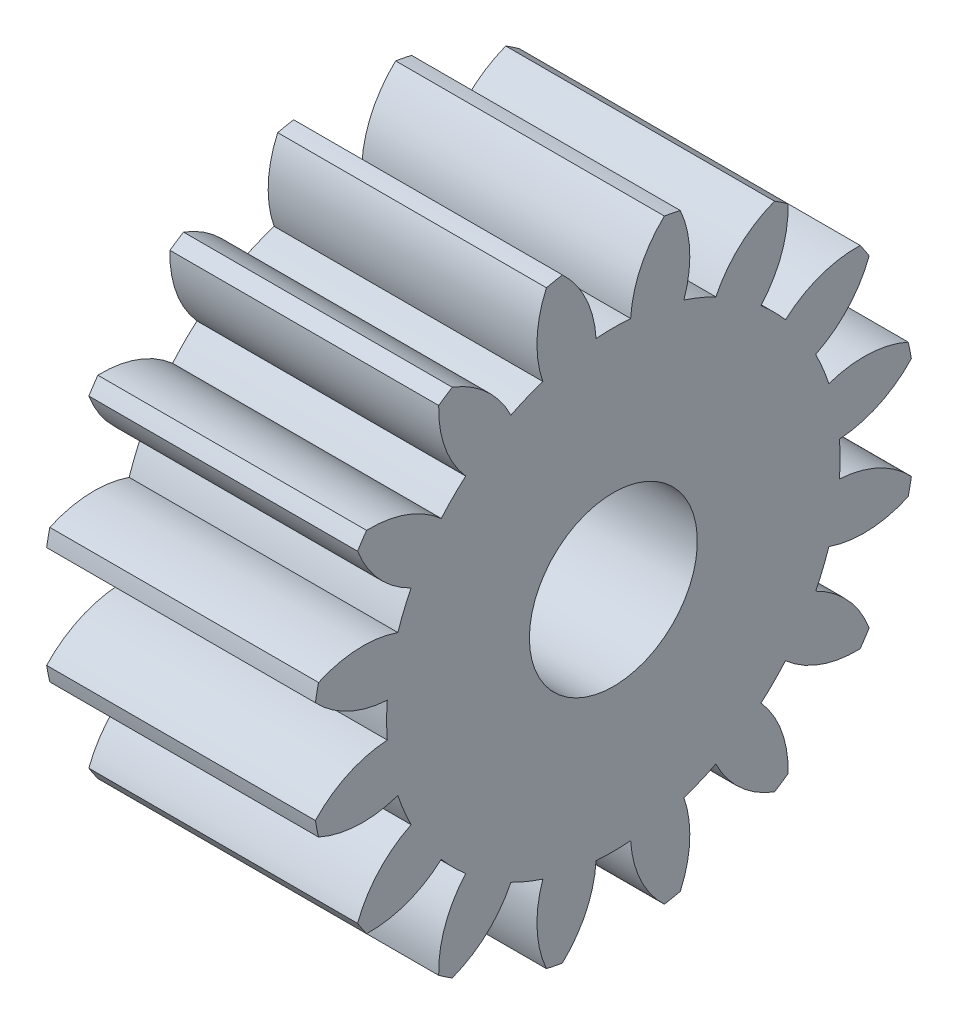
SolidWorks part; units mm, degrees
ref_plane "Plane1" through (0, 0, 0) normal (0, 0, 1) x (1, 0, 0)
ref_plane "Plane2" through (0, 0, 0) normal (0, 1, 0) x (1, 0, 0)
ref_plane "Plane3" through (0, 0, 0) normal (1, 0, 0) x (0, 0, -1)
sketch "HoldingSke" plane through (0, 0, 0) normal (0, 1, 0) x (1, 0, 0)
  line L0 (0, 0) -> (0.2403, -0.0689)
  line L1 (-15, 0) -> (100, 0) construction
  line L2 (0, 0) -> (-2.1039, 2.3779)
  line L3 (0, 0) -> (-11.863, 4.5341)
  line L4 (0, 0) -> (8.3015, 2.3804)
  line L5 (0, 0) -> (-46.8476, -17.4728)
  line L6 (0, 0) -> (-20.7241, -13.9826)
  line L7 (-2.1039, 2.3779) -> (8.6586, 51.2059)
  line L8 (-76.2, 54.61) -> (-73.4, 54.61)
  line L9 (-71.009, 38.7566) -> (-53.1078, 45.2721)
  line L10 (-76.2, 71.12) -> (104.1128, 71.12)
  line L11 (0, 0) -> (-25, 0)
  line L12 (-76.2, 101.6) -> (-76.073, 101.6)
  line L13 (24.9733, 27.94) -> (52.9518, 28.4284)
  line L14 (24.9733, 27.94) -> (24.9743, 27.94)
  line L15 (24.9733, 27.94) -> (100.4006, 29.5858)
  line L16 (-63.627, -4) -> (-12.827, -4)
  circle A0 centre (0, 0) radius 10
  circle A1 centre (0, 0) radius 26.999
  circle A2 centre (0, 0) radius 37.5
  circle A3 centre (0, 0) radius 10
  dimension "MHD" = 53.998
  dimension "Hub_dia" = 75
  dimension "Bore" = 20
  dimension "MBD" = 20
  dimension "Num_teeth" = 16
  dimension "Pitch" = 0.25
  dimension "Overall_len" = 50
  dimension "Show_teeth" = 16
  dimension "Thickness" = 25
  dimension "OAL" = 50.0001
  dimension "T_dim" = 2.8
  dimension "Ap" = 20
  dimension "H" = 19.05
  dimension "Pitch_radius" = 180.3128
  dimension "Width" = 25
  dimension "Backlash" = 0.127
  dimension "Addendum_fac" = 1
  dimension "Dedendum_fac" = 1.25
  dimension "Clearance_fac" = 0.25
  dimension "Dedendum_add" = 0.001
  dimension "Module" = 4
sketch "BasProSke" plane through (0, 0, 0) normal (0, 1, 0) x (1, 0, 0)
  line L0 (-10, 0) -> (60, 0) construction
  line L1 (0, 0) -> (0, 36)
  line L2 (0, 0) -> (32, 0)
  line L3 (32, 0) -> (32, 36)
  line L4 (32, 36) -> (0, 36)
  dimension "Thickness" = 32
  dimension "Diameter" = 72
revolve "Base-Revolve" add sketch "BasProSke" angle 360 about L0
sketch "TooCutSke" plane through (0, 0, 0) normal (1, 0, 0) x (0, 0, -1)
  line L1 (0, 0) -> (0, 107) construction
  line L2 (0, 0) -> (-3.3586, 31.8233) construction
  line L3 (0, 0) -> (-12.4339, 62.5094) construction
  line L4 (-3.3586, 31.8233) -> (-6.2169, 31.2547) construction
  arc A0 (2.0584, 26.9204) -> (-2.0584, 26.9204) centre (0, 0) ccw
  arc A1 (6.0943, 35.5062) -> (-6.0943, 35.5062) centre (0, 0) ccw
  circle A2 centre (0, 0) radius 32 construction
  circle A3 centre (0, 0) radius 30.0702 construction
  arc A4 (-2.0584, 26.9204) -> (-6.0943, 35.5062) centre (-14.8355, 26.1557) ccw
  arc A5 (6.0943, 35.5062) -> (2.0584, 26.9204) centre (14.8355, 26.1557) ccw
  dimension "Root_dia" = 53.998
  dimension "Overcut_dia" = 72.0508
  dimension "Pitch_dia" = 64
  dimension "Base_dia" = 60.1403
  dimension "Flank_rad" = 12.8
  dimension "Half_ang" = 11.25
  dimension "Half_CT" = 2.9143
extrude "ToothCut" cut sketch "TooCutSke" along normal through all
fillet "Breaks" [suppressed] radius 0.08
fillet "RootFillets" [suppressed] radius 1.001
pattern_circular "TeethCuts" count 16 every 22.5 about axis through (-10, 0, 0) along (1, 0, 0) of "ToothCut", "RootFillets", "Breaks"
sketch "HubNeaOneSke" plane through (0, 0, 0) normal (-1, 0, 0) x (0, 0, 1)
  circle A0 centre (0, 0) radius 26.999
  dimension "Diameter" = 53.998
extrude "HubNearOne" [suppressed] add sketch "HubNeaOneSke" along normal blind 18.0001
sketch "HubNeaBotSke" plane through (0, 0, 0) normal (-1, 0, 0) x (0, 0, 1)
  circle A0 centre (0, 0) radius 26.999
  dimension "Diameter" = 53.998
extrude "HubNearBoth" [suppressed] add sketch "HubNeaBotSke" along normal blind 9
ref_plane "FarPln" through (32, 0, 0) normal (1, 0, 0) x (0, 0, -1)
sketch "HubFarSke" plane through (32, 0, 0) normal (1, 0, 0) x (0, 0, -1)
  circle A0 centre (0, 0) radius 26.999
  dimension "Diameter" = 53.998
extrude "HubFar" [suppressed] add sketch "HubFarSke" along normal blind 9
sketch "BorSke" plane through (0, 0, 0) normal (1, 0, 0) x (0, 0, -1)
  circle A0 centre (0, 0) radius 10
  dimension "Diameter" = 20
extrude "Bore" cut sketch "BorSke" along normal mid plane 100.0001
sketch "KeySke" plane through (0, 0, 0) normal (1, 0, 0) x (0, 0, -1)
  line L0 (-3, 0) -> (-3, 12.8)
  line L1 (-3, 12.8) -> (3, 12.8)
  line L2 (3, 12.8) -> (3, 0)
  line L3 (0, 0) -> (0, 34) construction
  line L4 (-3, 0) -> (3, 0)
  dimension "Offset" = 12.8
  dimension "Width" = 6
extrude "Keyway" [suppressed] cut sketch "KeySke" along normal mid plane 100.0001
pattern_circular "Keyway2" [suppressed] count 2 every 90 about axis through (-10, 0, 0) along (1, 0, 0)
equation "' \"Module@HoldingSke\" = 6.35"
equation "' \"Num_teeth@HoldingSke\" = 12"
equation "' \"Ap@HoldingSke\" =  20"
equation "' \"Ap@HoldingSke\" = 20"
equation "' \"Width@HoldingSke\" = 0.5 * 25.4"
equation "' \"Hub_dia@HoldingSke\"= 1 * 25.4"
equation "' \"Hub_dia@HoldingSke\" = 1 * 25.4"
equation "' \"Overall_len@HoldingSke\" = 1.0 * 25.4"
equation "' \"Bore@HoldingSke\" = 0.75 * 25.4"
equation "' \"T_dim@HoldingSke\" = 0.1 * 25.4"
equation "' \"Width@KeySke\" = 0.25 * 25.4"
equation "' \"Show_teeth@HoldingSke\" = 13"
equation "' \"Backlash@HoldingSke\" = 0.009 * 25.4"
equation "' \"Addendum_fac@HoldingSke\" = 1.0"
equation "' \"Dedendum_fac@HoldingSke\" = 1.25"
equation "' \"Dedendum_add@HoldingSke\" = 0.00005 * 25.4"
equation "' \"Clearance_fac@HoldingSke\" = 0.25"
equation "\"Pitch@HoldingSke\" = 1 / \"Module@HoldingSke\""
equation "\"Overcut_dia@TooCutSke\" = (\"Num_teeth@HoldingSke\" + 2 * \"Addendum_fac@HoldingSke\") / \"Pitch@HoldingSke\" + 0.002 * 25.4"
equation "\"Pitch_dia@TooCutSke\" = \"Num_teeth@HoldingSke\" / \"Pitch@HoldingSke\""
equation "\"Base_dia@TooCutSke\" = \"Num_teeth@HoldingSke\" / \"Pitch@HoldingSke\" * cos((\"Ap@HoldingSke\"  * 3.14159265 / 180))"
equation "\"Root_dia@TooCutSke\" = (\"Num_teeth@HoldingSke\" + 2) / \"Pitch@HoldingSke\" - 2 * (\"Addendum_fac@HoldingSke\" + \"Dedendum_fac@HoldingSke\") / \"Pitch@HoldingSke\" - \"Dedendum_add@HoldingSke\" * 2"
equation "\"Half_ang@TooCutSke\" = 180 / \"Num_teeth@HoldingSke\""
equation "\"Half_CT@TooCutSke\" = \"Num_teeth@HoldingSke\" / \"Pitch@HoldingSke\" * sin((3.14159265 / 2 / \"Num_teeth@HoldingSke\")) / 2 - 7 * \"Backlash@HoldingSke\" / 4"
equation "\"Flank_rad@TooCutSke\" = \"Num_teeth@HoldingSke\" / \"Pitch@HoldingSke\" / 5"
equation "\"Radius@RootFillets\" = \"Clearance_fac@HoldingSke\" / \"Pitch@HoldingSke\" + \"Dedendum_add@HoldingSke\""
equation "\"Break_rad@Breaks\" = 0.02 / \"Pitch@HoldingSke\""
equation "\"Thickness@HoldingSke\" = \"Width@HoldingSke\""
equation "\"OAL@HoldingSke\" = \"Thickness@HoldingSke\""
equation "\"MHD@HoldingSke\" = (\"Num_teeth@HoldingSke\" + 2) / \"Pitch@HoldingSke\" - 2 * (\"Addendum_fac@HoldingSke\" + \"Dedendum_fac@HoldingSke\")  / \"Pitch@HoldingSke\" - \"Dedendum_add@HoldingSke\" * 2"
equation "\"MBD@HoldingSke\" = (\"Num_teeth@HoldingSke\" + 2) / \"Pitch@HoldingSke\" - 2 * (\"Addendum_fac@HoldingSke\" + \"Dedendum_fac@HoldingSke\")  / \"Pitch@HoldingSke\" - \"Dedendum_add@HoldingSke\" * 2 - 0.002 * 25.4"
equation "\"MHD@HoldingSke\" = ((sgn( \"MHD@HoldingSke\" - \"Hub_dia@HoldingSke\" )-1)*( \"MHD@HoldingSke\" - \"Hub_dia@HoldingSke\" ))/-2+ \"Hub_dia@HoldingSke\""
equation "\"MBD@HoldingSke\" = ((sgn( \"MBD@HoldingSke\" - \"Bore@HoldingSke\" )-1)*( \"MBD@HoldingSke\" - \"Bore@HoldingSke\" ))/-2+ \"Bore@HoldingSke\""
equation "\"OAL@HoldingSke\" = ((sgn( \"OAL@HoldingSke\" - \"Overall_len@HoldingSke\" )+1)*( \"OAL@HoldingSke\" - \"Overall_len@HoldingSke\" ))/2 + \"Overall_len@HoldingSke\" + 0.000002 * 25.4"
equation "\"Num_teeth@TeethCuts\" = int( \"Show_teeth@HoldingSke\" ) + 1"
equation "\"Num_teeth@TeethCuts\" = ((sgn( \"Num_teeth@TeethCuts\" - \"Num_teeth@HoldingSke\" )-1)*( \"Num_teeth@TeethCuts\" - \"Num_teeth@HoldingSke\" ))/-2+ \"Num_teeth@HoldingSke\""
equation "\"Num_teeth@TeethCuts\" = ((sgn( \"Num_teeth@TeethCuts\" - 2.0)+1)*( \"Num_teeth@TeethCuts\" - 2.0))/2 +2.0"
equation "\"Angle@TeethCuts\" = 360.0 / \"Num_teeth@HoldingSke\""
equation "\"Diameter@BasProSke\" = (\"Num_teeth@HoldingSke\" + 2 * \"Addendum_fac@HoldingSke\") / \"Pitch@HoldingSke\""
equation "' \"Fillet_rad@BasProSke\" =  \"Thickness@HoldingSke\" * 0.05"
equation "' \"Fillet_rad@BasProSke\" = \"Thickness@HoldingSke\" * 0.05"
equation "\"MHD@HoldingSke\" = ((sgn( \"MHD@HoldingSke\" - \"Root_dia@TooCutSke\" )-1)*( \"MHD@HoldingSke\" - \"Root_dia@TooCutSke\" ))/-2+ \"Root_dia@TooCutSke\""
equation "\"Diameter@HubNeaOneSke\" = \"MHD@HoldingSke\""
equation "\"Length@HubNearOne\" = \"OAL@HoldingSke\" - \"Thickness@BasProSke\""
equation "\"Diameter@HubNeaBotSke\" = \"MHD@HoldingSke\""
equation "\"Length@HubNearBoth\" = ( \"OAL@HoldingSke\" - \"Thickness@BasProSke\" ) / 2.0"
equation "\"Thickness@FarPln\" = \"Thickness@BasProSke\""
equation "\"Diameter@HubFarSke\" = \"MHD@HoldingSke\""
equation "\"Length@HubFar\" = ( \"OAL@HoldingSke\" - \"Thickness@BasProSke\" ) / 2.0"
equation "\"Diameter@BorSke\" = \"MBD@HoldingSke\""
equation "\"D1@Bore\" = \"OAL@HoldingSke\" * 2.0"
equation "\"D1@Keyway\" = \"OAL@HoldingSke\" * 2.0"
equation "\"Offset@KeySke\" = \"T_dim@HoldingSke\" + \"MBD@HoldingSke\" / 2.0"
